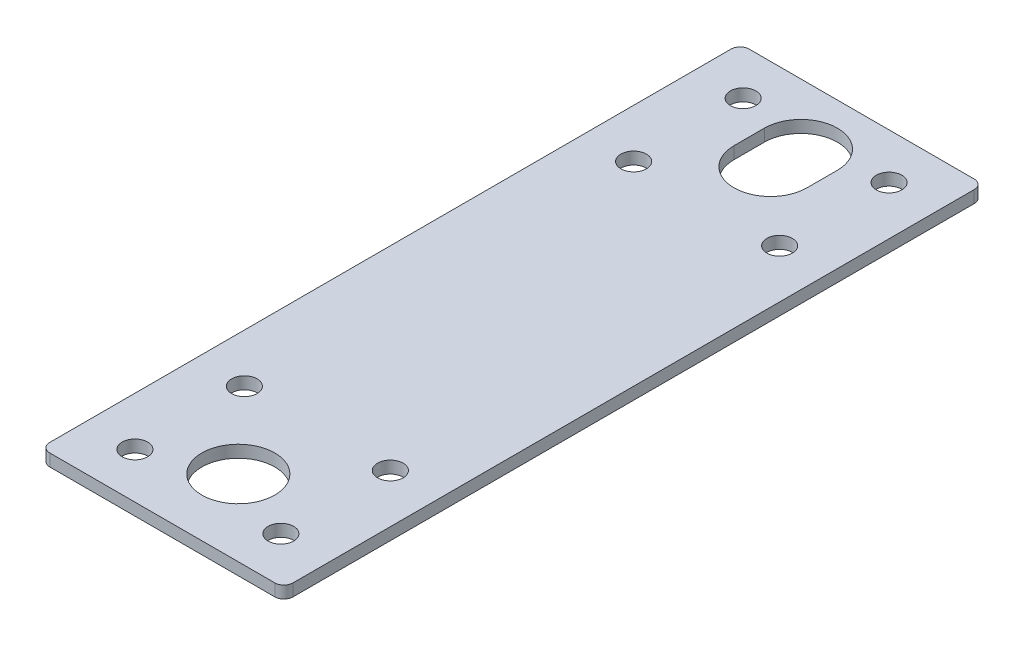
SolidWorks part; units mm, degrees
ref_plane "Front Plane" through (0, 0, 0) normal (0, 0, 1) x (1, 0, 0)
ref_plane "Top Plane" through (0, 0, 0) normal (0, 1, 0) x (1, 0, 0)
ref_plane "Right Plane" through (0, 0, 0) normal (1, 0, 0) x (0, 0, -1)
sketch "Sketch1" plane through (0, 0, 0) normal (0, 1, 0) x (1, 0, 0)
  line L0 (-60, 45) -> (60, 45) construction
  line L1 (-60, -57.5) -> (60, -57.5)
  line L2 (-60, -57.5) -> (-60, 57.5)
  line L3 (-60, 57.5) -> (60, 57.5)
  line L4 (60, -57.5) -> (60, 57.5)
  line L5 (-60, -57.5) -> (60, 57.5) construction
  line L6 (-60, 57.5) -> (60, -57.5) construction
  line L7 (0, 57.5) -> (0, -57.5) construction
  line L8 (-60, 0) -> (60, 0) construction
  line L9 (-60, -45) -> (60, -45) construction
  line L10 (-20, 57.5) -> (-20, -57.5)
  circle A0 centre (-40, 45) radius 6
  circle A3 centre (-40, -45) radius 6
  point P0 (0, 0)
  dimension "D1" = 12
  dimension "D2" = 20
  dimension "D3" = 120
  dimension "D4" = 90
  dimension "D5" = 115
  dimension "D6" = 40
extrude "Boss-Extrude1" add sketch "Sketch1" along normal blind 2 contours L10 L3 L2 L1 A0 A3
sketch "Sketch2" plane through (0, 2, 0) normal (0, 1, 0) x (1, 0, 0)
  line L0 (-40, 57.5) -> (-40, -38) construction
  line L2 (-60, -32) -> (60, -32) construction
  line L5 (-60, -41) -> (60, -41) construction
  line L8 (-60, 0) -> (60, 0) construction
  circle A0 centre (-52, -32) radius 2.1
  circle A1 centre (-28, -32) radius 2.1
  circle A2 centre (-28, -50) radius 2.1
  circle A3 centre (-52, -50) radius 2.1
  circle A8 centre (-40, -45) radius 6 construction
  circle A13 centre (-28, 50) radius 2.1
  circle A14 centre (-52, 50) radius 2.1
  circle A15 centre (-52, 32) radius 2.1
  circle A16 centre (-28, 32) radius 2.1
  dimension "D1" = 4.2
  dimension "D2" = 24
  dimension "D4" = 5
  dimension "D3" = 9
  dimension "D5" = 41
extrude "Cut-Extrude1" cut sketch "Sketch2" against normal through all
sketch "Sketch3" plane through (0, 2, 0) normal (0, 1, 0) x (1, 0, 0)
  line L0 (-40, 57.5) -> (-40, 29.2629) construction
  line L1 (-60, 57.5) -> (-20, 57.5) construction
  line L2 (-40, 47.5) -> (-40, 42.5) construction
  line L3 (-34, 47.5) -> (-34, 42.5)
  line L4 (-46, 47.5) -> (-46, 42.5)
  arc A0 (-34, 47.5) -> (-46, 47.5) centre (-40, 47.5) ccw
  arc A1 (-46, 42.5) -> (-34, 42.5) centre (-40, 42.5) ccw
  circle A2 centre (-40, 45) radius 6 construction
  point P6 (-40, 45)
  dimension "D1" = 6
  dimension "D2" = 5
extrude "Cut-Extrude2" cut sketch "Sketch3" against normal through all
fillet "Fillet1" radius 1.5 4 edges at (-20, 1, 57.5) (-60, 1, 57.5) (-20, 1, -57.5) (-60, 1, -57.5)
